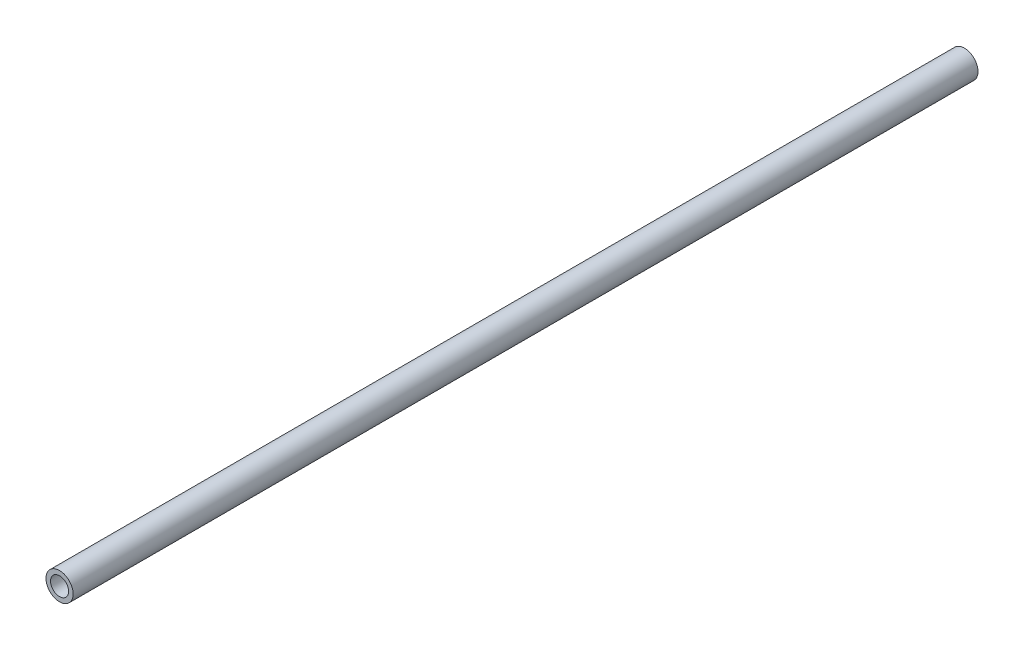
SolidWorks part; units mm, degrees
ref_plane "Face" through (0, 0, 0) normal (0, 0, 1) x (1, 0, 0)
ref_plane "Dessus" through (0, 0, 0) normal (0, 1, 0) x (1, 0, 0)
ref_plane "Droite" through (0, 0, 0) normal (1, 0, 0) x (0, 0, -1)
sketch "Esquisse1" plane through (0, 0, 0) normal (0, 0, 1) x (1, 0, 0)
  circle A0 centre (0, 0) radius 2
  circle A1 centre (0, 0) radius 3
  dimension "D1" = 1
  dimension "D2" = 6
extrude "Boss.-Extru.1" add sketch "Esquisse1" along normal blind 200
